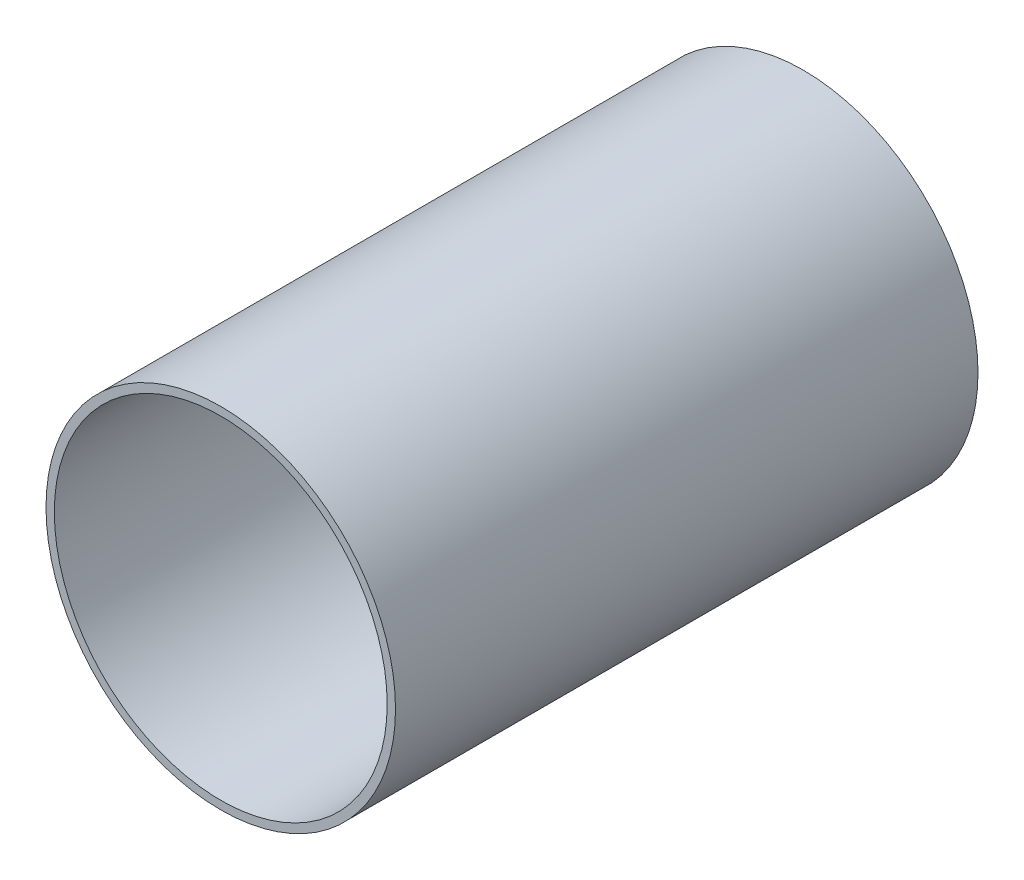
SolidWorks part; units mm, degrees
ref_plane "Front Plane" through (0, 0, 0) normal (0, 0, 1) x (1, 0, 0)
ref_plane "Top Plane" through (0, 0, 0) normal (0, 1, 0) x (1, 0, 0)
ref_plane "Right Plane" through (0, 0, 0) normal (1, 0, 0) x (0, 0, -1)
sketch "Sketch1" plane through (0, 0, 0) normal (0, 0, 1) x (1, 0, 0)
  circle A0 centre (0, 0) radius 20
  circle A1 centre (0, 0) radius 21
  dimension "D1" = 40
  dimension "D2" = 1
extrude "Boss-Extrude1" add sketch "Sketch1" along normal blind 70
